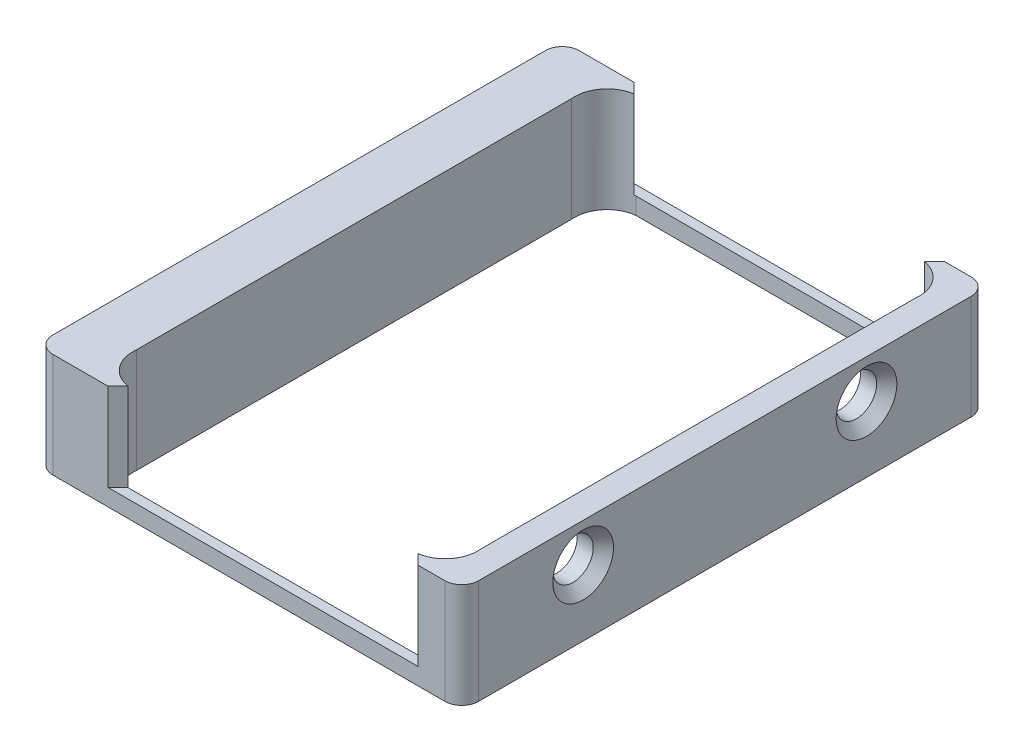
SolidWorks part; units mm, degrees
ref_plane "Front Plane" through (0, 0, 0) normal (0, 0, 1) x (1, 0, 0)
ref_plane "Top Plane" through (0, 0, 0) normal (0, 1, 0) x (1, 0, 0)
ref_plane "Right Plane" through (0, 0, 0) normal (1, 0, 0) x (0, 0, -1)
other "Configuration Table"
sketch "草图1" plane through (0, 0, 0) normal (0, 1, 0) x (1, 0, 0)
  line L0 (0, -75.1) -> (0, 75.1) construction
  line L1 (-51.1, 0) -> (51.1, 0) construction
  line L2 (-42.5, 75.1) -> (42.5, 75.1)
  line L3 (-51.1, -64.5) -> (-51.1, 64.5)
  line L4 (-42.5, -75.1) -> (42.5, -75.1)
  line L5 (51.1, -64.5) -> (51.1, 64.5)
  line L6 (-51.1, 0) -> (-67.3, 0) construction
  line L7 (-67.3, -78) -> (-67.3, 78)
  line L8 (51.1, 0) -> (58.9, 0) construction
  line L9 (58.9, -78) -> (58.9, 78)
  line L10 (-67.3, 78) -> (58.9, 78)
  line L11 (-67.3, -78) -> (58.9, -78)
  arc A4 (-51.1, 64.5) -> (-42.5, 75.1) centre (-41.5, 65.5) cw
  arc A5 (-51.1, -64.5) -> (-42.5, -75.1) centre (-41.5, -65.5) ccw
  arc A6 (42.5, -75.1) -> (51.1, -64.5) centre (41.5, -65.5) ccw
  arc A7 (42.5, 75.1) -> (51.1, 64.5) centre (41.5, 65.5) cw
  point P4 (0, 0)
  point P9 (0, 0)
  point P12 (0, 75.1)
  point P15 (-51.1, 0)
  point P27 (-67.3, 0)
  point P31 (58.9, 0)
  dimension "D1" = 16.2
  dimension "D4" = 85
  dimension "D2" = 51.1
  dimension "D3" = 7.8
  dimension "D5" = 129
extrude "凸台-拉伸1" add sketch "草图1" along normal blind 31 contours L11 L9 L10 L7
sketch "草图2" plane through (0, 31, 0) normal (0, 1, 0) x (1, 0, 0)
  line L0 (0, 0) -> (0, 78) construction
  line L1 (58.9, 78) -> (-67.3, 78) construction
  line L2 (-46, 78) -> (46, 78)
  line L3 (-43.1, 75.1) -> (43.1, 75.1)
  line L4 (-43.1, 75.1) -> (-42.7809, 74.7809)
  line L5 (42.5, 75.1) -> (-42.5, 75.1) construction
  line L6 (-43.1, 75.1) -> (-46, 78)
  line L7 (43.1, 75.1) -> (46, 78)
  line L8 (0, 0) -> (58.9, 0) construction
  line L9 (58.9, -78) -> (58.9, 78) construction
  line L14 (-42.7809, 74.7809) -> (-42.5, 75.1)
  line L15 (43.1, 75.1) -> (42.8724, 74.8724)
  line L16 (42.8724, 74.8724) -> (42.5, 75.1)
  line L17 (42.8724, -74.8724) -> (42.5, -75.1)
  line L18 (43.1, -75.1) -> (42.8724, -74.8724)
  line L19 (-42.7809, -74.7809) -> (-42.5, -75.1)
  line L20 (-43.1, -75.1) -> (-42.7809, -74.7809)
  line L21 (-43.1, -75.1) -> (43.1, -75.1)
  line L22 (-43.1, -75.1) -> (-46, -78)
  line L23 (-46, -78) -> (46, -78)
  line L24 (43.1, -75.1) -> (46, -78)
  point P8 (0, 78)
  point P14 (0, 75.1)
extrude "切除-拉伸1" cut sketch "草图2" against normal blind 26
fillet "圆角1" radius 5 4 edges at (-67.3, 15.5, -78) (58.9, 15.5, -78) (58.9, 15.5, 78) (-67.3, 15.5, 78)
sketch "草图5" plane through (58.9, 0, 0) normal (1, 0, 0) x (0, 0, -1)
  line L0 (-78, 0) -> (-78, 31) construction
  line L1 (-73, 0) -> (73, 0) construction
  line L2 (78, 31) -> (78, 0) construction
  point P0 (42, 19.55)
  point P2 (-42, 19.55)
  dimension "D1" = 36
  dimension "D2" = 19.55
  dimension "D3" = 36
  dimension "D4" = 19.55
hole_wizard "Ø12.0mm 暗销孔1" positions "草图5" profile "草图4" hole size "Ø12.0" standard "ANSI Metric"
sketch "草图4" plane through (58.9, 19.55, -42) normal (0, 1, 0) x (0, 0, -1)
  line L0 (0, 0) -> (0, 20.6052)
  line L1 (0, 20.6052) -> (6, 17)
  line L2 (6, 17) -> (6, 0)
  line L5 (6, 0) -> (0, 0)
  line L10 (0, 20.6052) -> (-6, 17) construction
  line L11 (0, -6.35) -> (0, 107.95) construction
  dimension "孔直径" = 12
  dimension "孔深度" = 17
  dimension "导头角度" = 118
sketch "草图6" plane through (-67.3, 0, 0) normal (-1, 0, 0) x (0, 0, 1)
  line L0 (0, 0) -> (0, 13.95) construction
  line L1 (0, 13.95) -> (-11, 13.95) construction
  circle A2 centre (-11, 13.95) radius 2.1
  circle A3 centre (11, 13.95) radius 2.1
  point P4 (0, 13.45)
  dimension "D1" = 4.2
extrude "切除-拉伸2" cut sketch "草图6" against normal blind 10
sketch "草图7" plane through (0, 0, 0) normal (0, -1, 0) x (1, 0, 0)
  circle A0 centre (-58.4934, 70.9643) radius 2.1
  circle A1 centre (53.705, 73.3482) radius 2.1
  circle A2 centre (-58.4934, -70.9643) radius 2.1
  circle A3 centre (53.705, -73.3482) radius 2.1
extrude "切除-拉伸3" cut sketch "草图7" against normal blind 10
chamfer "倒角1" distance 3 angle 45 2 edges at (58.9, 19.55, 36) (58.9, 19.55, -48)
